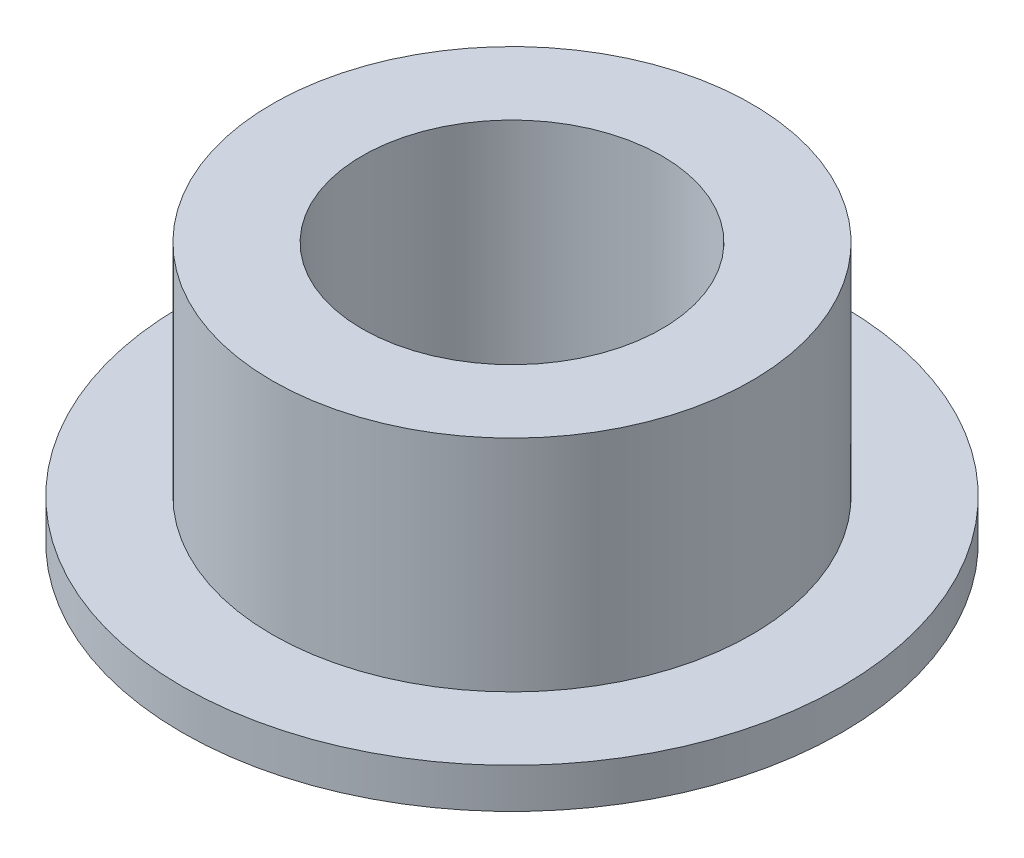
SolidWorks part; units mm, degrees
ref_plane "Ön Düzlem" through (0, 0, 0) normal (0, 0, 1) x (1, 0, 0)
ref_plane "Üst Düzlem" through (0, 0, 0) normal (0, 1, 0) x (1, 0, 0)
ref_plane "Sağ Düzlem" through (0, 0, 0) normal (1, 0, 0) x (0, 0, -1)
sketch "Sketch1" plane through (0, 0, 0) normal (0, 1, 0) x (1, 0, 0)
  circle A0 centre (0, 0) radius 16.5
  dimension "D1" = 33
extrude "Boss-Extrude1" add sketch "Sketch1" along normal blind 2
sketch "Sketch2" plane through (0, 2, 0) normal (0, 1, 0) x (1, 0, 0)
  circle A0 centre (0, 0) radius 12
  dimension "D1" = 24
extrude "Boss-Extrude2" add sketch "Sketch2" along normal blind 11
sketch "Sketch3" plane through (0, 0, 0) normal (0, -1, 0) x (1, 0, 0)
  circle A0 centre (0, 0) radius 9
  dimension "D1" = 18
extrude "Cut-Extrude1" cut sketch "Sketch3" against normal blind 1
sketch "Sketch4" plane through (0, 13, 0) normal (0, 1, 0) x (1, 0, 0)
  circle A0 centre (0, 0) radius 7.5
  dimension "D1" = 15
extrude "Cut-Extrude2" cut sketch "Sketch4" against normal blind 12
